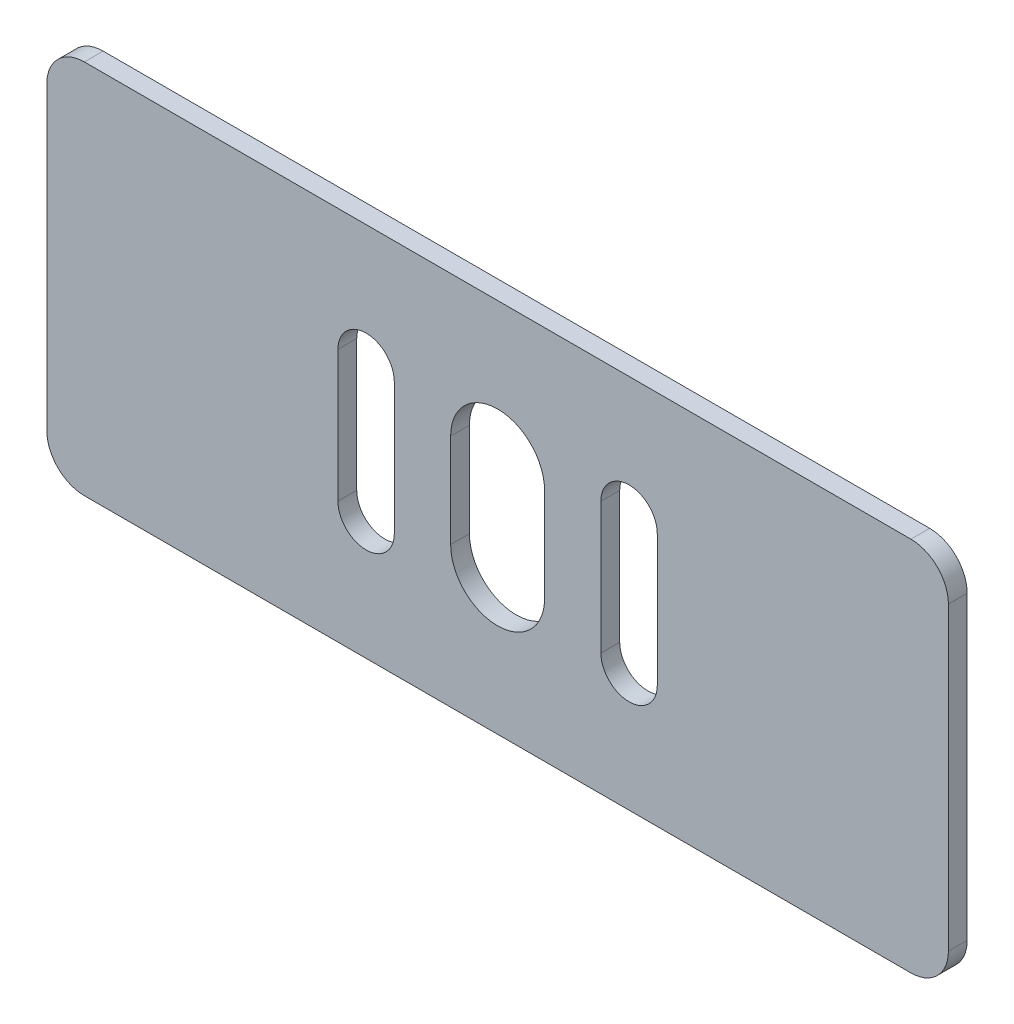
SolidWorks part; units mm, degrees
ref_plane "Front Plane" through (0, 0, 0) normal (0, 0, 1) x (1, 0, 0)
ref_plane "Top Plane" through (0, 0, 0) normal (0, 1, 0) x (1, 0, 0)
ref_plane "Right Plane" through (0, 0, 0) normal (1, 0, 0) x (0, 0, -1)
sketch "Sketch1" plane through (0, 0, 0) normal (0, 0, 1) x (1, 0, 0)
  line L0 (0, -2.5) -> (0, 2.5) construction
  line L1 (22, -10) -> (-22, -10)
  line L2 (24, -8) -> (24, 8)
  line L3 (22, 10) -> (-22, 10)
  line L4 (-24, -8) -> (-24, 8)
  line L5 (24, -10) -> (-24, 10) construction
  line L6 (24, 10) -> (-24, -10) construction
  line L7 (-2.5, -2.5) -> (-2.5, 2.5)
  line L8 (2.5, -2.5) -> (2.5, 2.5)
  line L9 (-7, -3.5) -> (-7, 3.5) construction
  line L10 (-8.5, -3.5) -> (-8.5, 3.5)
  line L11 (-5.5, -3.5) -> (-5.5, 3.5)
  line L12 (7, -3.5) -> (7, 3.5) construction
  line L13 (5.5, -3.5) -> (5.5, 3.5)
  line L14 (8.5, -3.5) -> (8.5, 3.5)
  arc A0 (-22, 10) -> (-24, 8) centre (-22, 8) ccw
  arc A1 (24, 8) -> (22, 10) centre (22, 8) ccw
  arc A2 (22, -10) -> (24, -8) centre (22, -8) ccw
  arc A3 (-22, -10) -> (-24, -8) centre (-22, -8) cw
  arc A4 (-2.5, -2.5) -> (2.5, -2.5) centre (0, -2.5) ccw
  arc A5 (2.5, 2.5) -> (-2.5, 2.5) centre (0, 2.5) ccw
  arc A6 (-8.5, -3.5) -> (-5.5, -3.5) centre (-7, -3.5) ccw
  arc A7 (-5.5, 3.5) -> (-8.5, 3.5) centre (-7, 3.5) ccw
  arc A8 (5.5, -3.5) -> (8.5, -3.5) centre (7, -3.5) ccw
  arc A9 (8.5, 3.5) -> (5.5, 3.5) centre (7, 3.5) ccw
  point P0 (0, 0)
  point P20 (0, 0)
  point P26 (-7, 0)
  point P33 (7, 0)
  point P39 (0, 0)
  point P40 (0, 0)
  point P41 (0, 0)
  dimension "D3" = 2
  dimension "D4" = 10
  dimension "D10" = 10
  dimension "D11" = 10
  dimension "D1" = 48
  dimension "D2" = 20
  dimension "D5" = 5
  dimension "D6" = 3
  dimension "D7" = 3
  dimension "D8" = 3
  dimension "D9" = 3
extrude "Boss-Extrude1" add sketch "Sketch1" along normal mid plane 1
